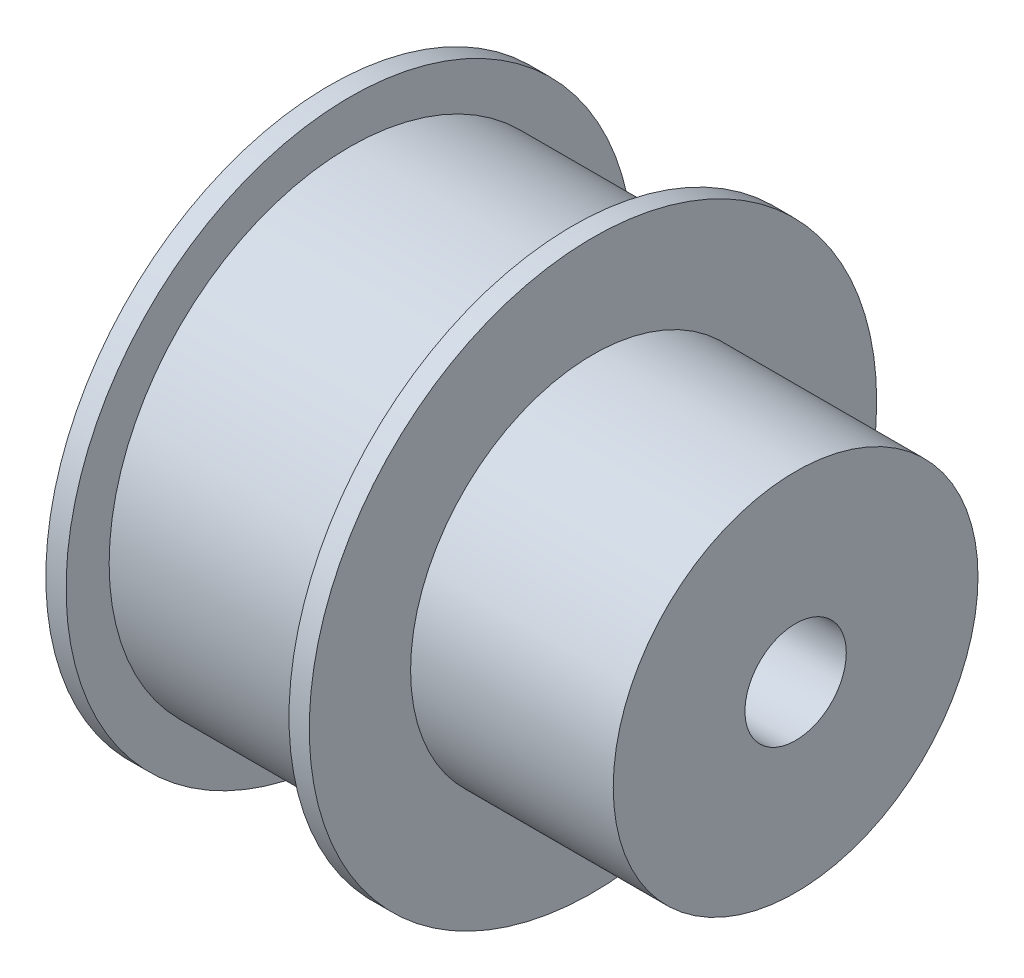
SolidWorks part; units mm, degrees
ref_plane "Front Plane" through (0, 0, 0) normal (0, 0, 1) x (1, 0, 0)
ref_plane "Top Plane" through (0, 0, 0) normal (0, 1, 0) x (1, 0, 0)
ref_plane "Right Plane" through (0, 0, 0) normal (1, 0, 0) x (0, 0, -1)
sketch "Sketch1" plane through (0, 0, 0) normal (1, 0, 0) x (0, 0, -1)
  circle A0 centre (0, 0) radius 14
  dimension "D1" = 28
extrude "Boss-Extrude1" add sketch "Sketch1" along normal blind 1
sketch "Sketch2" plane through (1, 0, 0) normal (1, 0, 0) x (0, 0, -1)
  circle A0 centre (0, 0) radius 11.875
  dimension "D1" = 23.75
extrude "Boss-Extrude2" add sketch "Sketch2" along normal blind 11
sketch "Sketch3" plane through (12, 0, 0) normal (1, 0, 0) x (0, 0, -1)
  circle A0 centre (0, 0) radius 14
  dimension "D1" = 28
extrude "Boss-Extrude3" add sketch "Sketch3" along normal blind 1
sketch "Sketch4" plane through (13, 0, 0) normal (1, 0, 0) x (0, 0, -1)
  circle A0 centre (0, 0) radius 9
  dimension "D1" = 18
extrude "Boss-Extrude4" add sketch "Sketch4" along normal blind 10
sketch "Sketch5" plane through (23, 0, 0) normal (1, 0, 0) x (0, 0, -1)
  circle A0 centre (0, 0) radius 2.5
  dimension "D1" = 5
extrude "Cut-Extrude1" cut sketch "Sketch5" against normal through all
equation "\"D1@Sketch3\"=\"D1@Sketch1\""
equation "\"D1@Boss-Extrude4\"=23-2-11"
